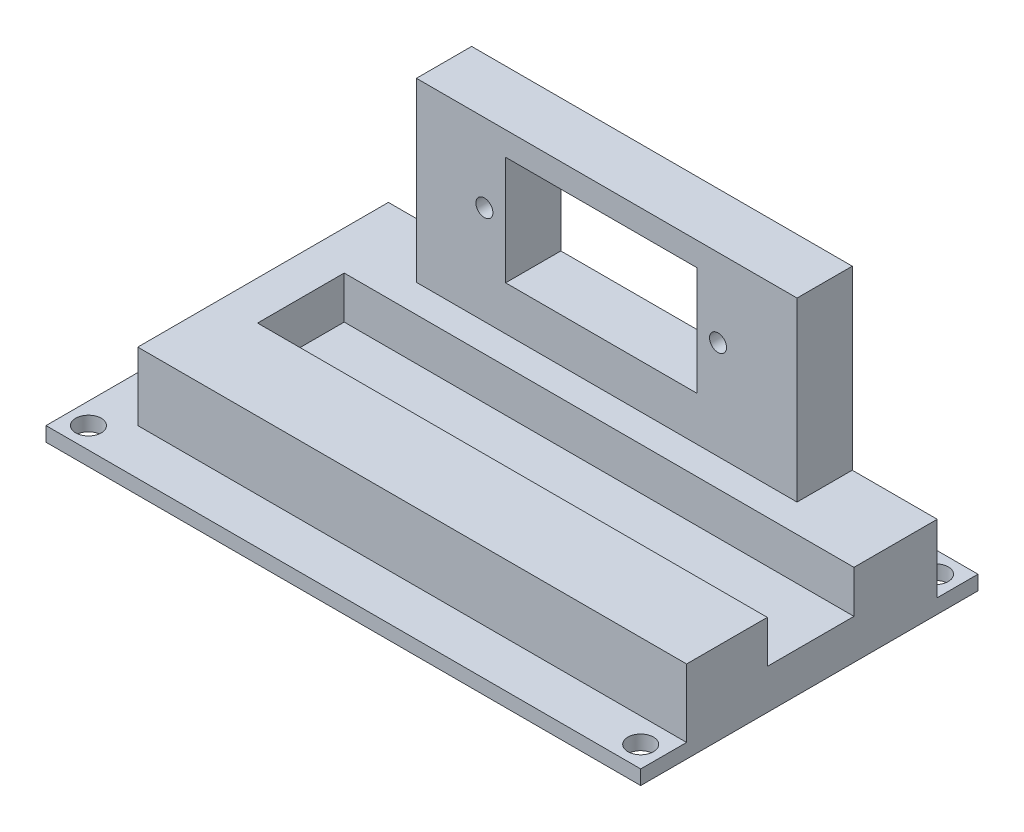
SolidWorks part; units mm, degrees
ref_plane "Front Plane" through (0, 0, 0) normal (0, 0, 1) x (1, 0, 0)
ref_plane "Top Plane" through (0, 0, 0) normal (0, 1, 0) x (1, 0, 0)
ref_plane "Right Plane" through (0, 0, 0) normal (1, 0, 0) x (0, 0, -1)
sketch "Sketch2" plane through (0, 0, 0) normal (0, 1, 0) x (1, 0, 0)
  line L1 (-35, 19.85) -> (35, 19.85)
  line L2 (-35, 19.85) -> (-35, -19.85)
  line L3 (-35, -19.85) -> (35, -19.85)
  line L4 (35, 19.85) -> (35, -19.85)
  dimension "D1" = 39.7
  dimension "D2" = 70
  dimension "D3" = 19.85
  dimension "D4" = 35
extrude "Boss-Extrude1" add sketch "Sketch2" along normal blind 1.7
sketch "Sketch3" plane through (0, 1.7, 0) normal (0, 1, 0) x (1, 0, 0)
  line L0 (35, 15.05) -> (-29.6, 15.05)
  line L1 (35, -19.85) -> (35, 19.85) construction
  line L2 (-29.6, 15.05) -> (-29.6, -14.45)
  line L3 (-29.6, -14.45) -> (35, -14.45)
  line L4 (35, -14.45) -> (35, -4.95)
  line L5 (35, -4.95) -> (-25, -4.95)
  line L6 (-25, -4.95) -> (-25, 5.25)
  line L7 (-25, 5.25) -> (35, 5.25)
  line L8 (35, 15.05) -> (35, 5.25)
  line L9 (35, 19.85) -> (-35, 19.85) construction
  dimension "D1" = 29.5
  dimension "D2" = 9.5
  dimension "D3" = 9.8
  dimension "D4" = 60
  dimension "D5" = 64.6
  dimension "D6" = 4.8
extrude "Boss-Extrude2" add sketch "Sketch3" along normal blind 8
sketch "Sketch6" plane through (0, 1.7, 0) normal (0, 1, 0) x (1, 0, 0)
  line L1 (-25, 5.25) -> (35, 5.25)
  line L2 (-25, 5.25) -> (-25, -4.95)
  line L3 (-25, -4.95) -> (35, -4.95)
  line L4 (35, 5.25) -> (35, -4.95)
extrude "Boss-Extrude3" add sketch "Sketch6" along normal blind 3
sketch "Sketch7" plane through (0, 9.7, 0) normal (0, 1, 0) x (1, 0, 0)
  line L0 (35, 15.05) -> (-29.6, 15.05) construction
  line L1 (-19.8, 15.05) -> (25, 15.05)
  line L2 (-19.8, 15.05) -> (-19.8, 8.55)
  line L3 (-19.8, 8.55) -> (25, 8.55)
  line L4 (25, 15.05) -> (25, 8.55)
  line L5 (35, 5.25) -> (35, 15.05) construction
  dimension "D1" = 6.5
  dimension "D2" = 44.8
  dimension "D3" = 10
extrude "Boss-Extrude4" add sketch "Sketch7" along normal blind 20.8
sketch "Sketch8" plane through (0, 0, -15.05) normal (0, 0, -1) x (-1, 0, 0)
  line L0 (-25, 30.5) -> (19.8, 30.5) construction
  line L1 (-13.2, 27.7) -> (9.3, 27.7)
  line L2 (-13.2, 27.7) -> (-13.2, 14.9)
  line L3 (-13.2, 14.9) -> (9.3, 14.9)
  line L4 (9.3, 27.7) -> (9.3, 14.9)
  line L5 (-25, 30.5) -> (-25, 9.7) construction
  dimension "D1" = 22.5
  dimension "D2" = 12.8
  dimension "D3" = 2.8
  dimension "D4" = 11.8
extrude "Cut-Extrude1" cut sketch "Sketch8" against normal up to next
sketch "Sketch9" plane through (0, 0, -15.05) normal (0, 0, -1) x (-1, 0, 0)
  line L0 (-25, 30.5) -> (-25, 9.7) construction
  line L1 (-25, 30.5) -> (19.8, 30.5) construction
  line L7 (-13.2, 27.7) -> (-13.2, 14.9) construction
  line L8 (9.3, 14.9) -> (9.3, 27.7) construction
  circle A0 centre (-15.7, 21.3) radius 1
  circle A1 centre (11.8, 21.3) radius 1
  point P10 (-13.2, 21.3)
  point P13 (9.3, 21.3)
  dimension "D1" = 2
  dimension "D6" = 2.5
  dimension "D2" = 9.3
  dimension "D4" = 9.2
  dimension "D5" = 27.5
  dimension "D7" = 2.5
  dimension "D3" = 2
extrude "Cut-Extrude2" cut sketch "Sketch9" against normal up to next
sketch "Sketch10" plane through (0, 0, 0) normal (0, -1, 0) x (1, 0, 0)
  line L0 (-35, -19.85) -> (-35, 19.85) construction
  line L1 (-35, 19.85) -> (35, 19.85) construction
  circle A0 centre (-32.5, 17.35) radius 1.5
  circle A1 centre (32.5, 17.35) radius 1.5
  dimension "D1" = 3
  dimension "D2" = 2.5
  dimension "D3" = 2.5
  dimension "D4" = 2
extrude "Cut-Extrude3" cut sketch "Sketch10" against normal up to next
mirror "Mirror1" about plane through (0, 0, 0) normal (0, 0, 1) of "Cut-Extrude3"
sketch "Sketch13" plane through (0, 0, 0) normal (0, -1, 0) x (1, 0, 0)
  line L0 (35, 19.85) -> (35, -19.85) construction
  line L1 (-27.8, -7.85) -> (32.2, -7.85)
  line L2 (-27.8, -7.85) -> (-27.8, -13.35)
  line L3 (-27.8, -13.35) -> (32.2, -13.35)
  line L4 (32.2, -7.85) -> (32.2, -13.35)
  line L5 (35, -19.85) -> (-35, -19.85) construction
  dimension "D1" = 60
  dimension "D2" = 5.5
  dimension "D3" = 2.8
  dimension "D4" = 6.5
extrude "Cut-Extrude4" cut sketch "Sketch13" against normal blind 4.5
sketch "Sketch14" plane through (0, 0, 0) normal (0, -1, 0) x (1, 0, 0)
  line L0 (35, 19.85) -> (35, -19.85) construction
  line L1 (32.5, 12.85) -> (-27.5, 12.85)
  line L2 (32.5, 12.85) -> (32.5, 7.35)
  line L3 (32.5, 7.35) -> (-27.5, 7.35)
  line L4 (-27.5, 12.85) -> (-27.5, 7.35)
  line L5 (-35, 19.85) -> (35, 19.85) construction
  dimension "D1" = 5.5
  dimension "D2" = 60
  dimension "D3" = 2.5
  dimension "D4" = 7
extrude "Cut-Extrude5" cut sketch "Sketch14" against normal blind 4.5
